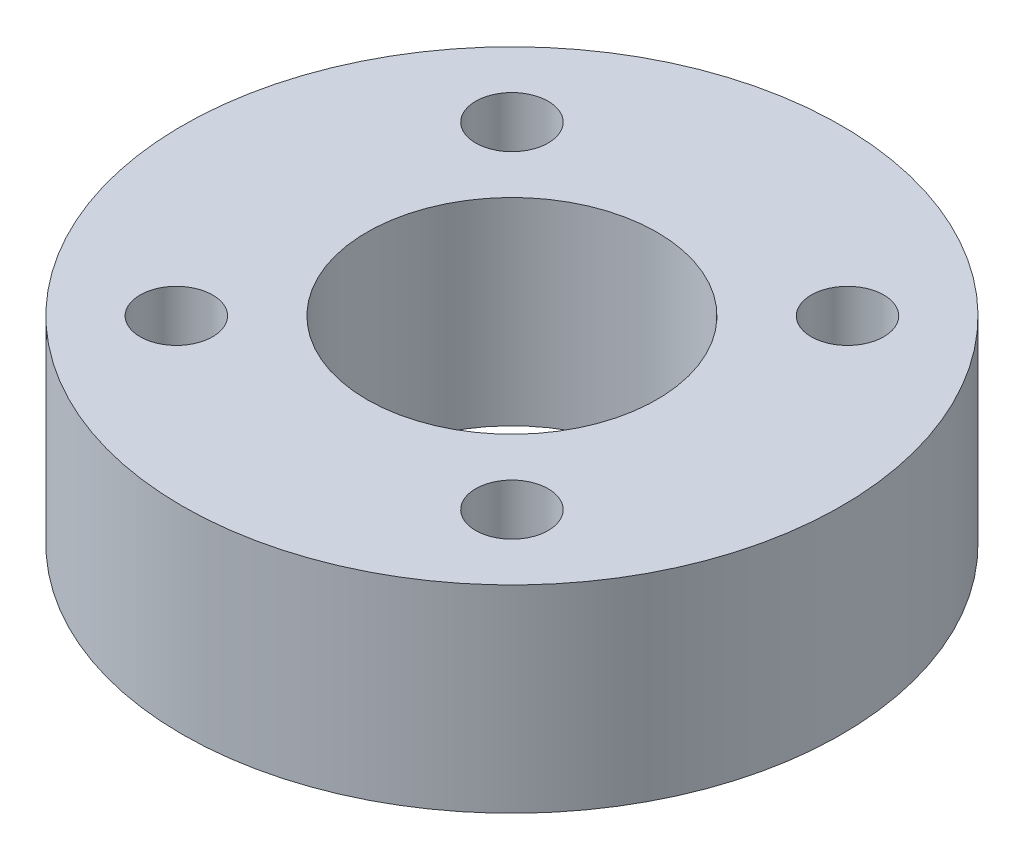
SolidWorks part; units mm, degrees
material "2024-T3"
ref_plane "正面" through (0, 0, 0) normal (0, 0, 1) x (1, 0, 0)
ref_plane "平面" through (0, 0, 0) normal (0, 1, 0) x (1, 0, 0)
ref_plane "右側面" through (0, 0, 0) normal (1, 0, 0) x (0, 0, -1)
sketch "ｽｹｯﾁ1" plane through (0, 0, 0) normal (0, 1, 0) x (1, 0, 0)
  circle A0 centre (0, 0) radius 25
  dimension "D1" = 50
extrude "ﾎﾞｽ - 押し出し1" add sketch "ｽｹｯﾁ1" along normal blind 15
sketch "ｽｹｯﾁ2" plane through (0, 15, 0) normal (0, 1, 0) x (1, 0, 0)
  circle A0 centre (0, 0) radius 11
  dimension "D1" = 22
extrude "ｶｯﾄ - 押し出し1" cut sketch "ｽｹｯﾁ2" against normal through all
sketch "ｽｹｯﾁ3" plane through (0, 15, 0) normal (0, 1, 0) x (1, 0, 0)
  line L1 (-12.7279, 12.7279) -> (12.7279, 12.7279)
  line L2 (-12.7279, 12.7279) -> (-12.7279, -12.7279)
  line L3 (-12.7279, -12.7279) -> (12.7279, -12.7279)
  line L4 (12.7279, 12.7279) -> (12.7279, -12.7279)
  circle A0 centre (-12.7279, 12.7279) radius 2.5
  circle A1 centre (-12.7279, -12.7279) radius 2.5
  circle A2 centre (12.7279, 12.7279) radius 2.5
  circle A3 centre (12.7279, -12.7279) radius 2.5
  circle A4 centre (0, 0) radius 18
  point P0 (-12.7279, 12.7279)
  point P1 (12.7279, -12.7279)
  point P2 (-12.7279, -12.7279)
  point P3 (12.7279, 12.7279)
  dimension "D2" = 5
  dimension "D3" = 5
  dimension "D4" = 5
  dimension "D5" = 5
  dimension "D1" = 36
hole_wizard "M5 すきま穴1" positions "ｽｹｯﾁ3" profile "ｽｹｯﾁ4" hole size "M5" standard "JIS" end condition through all
sketch "ｽｹｯﾁ4" plane through (-12.7279, 15, -12.7279) normal (1, 0, 0) x (0, 0, 1)
  line L0 (0, 0) -> (0, 15)
  line L1 (0, 15) -> (2.75, 15)
  line L2 (2.75, 15) -> (2.75, 0)
  line L5 (2.75, 0) -> (0, 0)
  line L11 (0, -6.35) -> (0, 107.95) construction
  dimension "通し穴の直径" = 5.5
  dimension "通し穴の深さ" = 15
